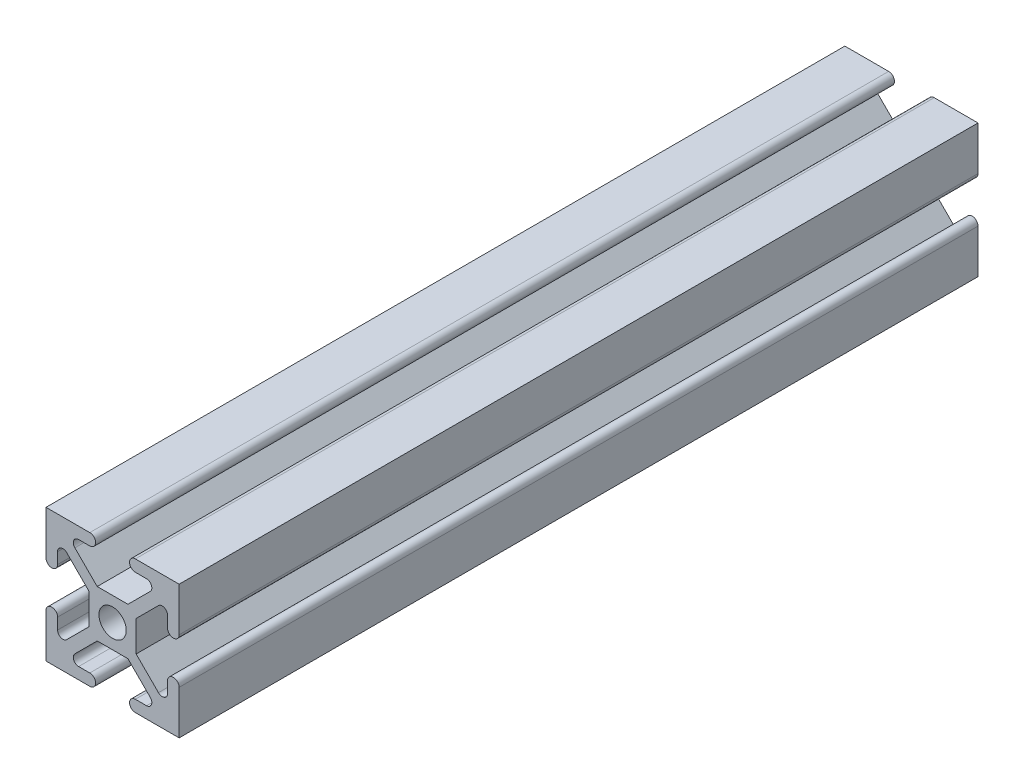
SolidWorks part; units mm, degrees
ref_plane "Front Plane" through (0, 0, 0) normal (0, 0, 1) x (1, 0, 0)
ref_plane "Top Plane" through (0, 0, 0) normal (0, 1, 0) x (1, 0, 0)
ref_plane "Right Plane" through (0, 0, 0) normal (1, 0, 0) x (0, 0, -1)
sketch "Sketch1" plane through (0, 0, 0) normal (0, 0, 1) x (1, 0, 0)
  line L2 (-12.7, -12.7) -> (-4.3434, -12.7)
  line L3 (-4.3434, -10.4902) -> (-6.4748, -10.4902)
  line L4 (-7.1932, -8.7558) -> (-2.9332, -4.4958)
  line L5 (-2.9332, -4.4958) -> (2.9332, -4.4958)
  line L6 (2.9332, -4.4958) -> (7.1932, -8.7558)
  line L7 (6.4748, -10.4902) -> (4.3434, -10.4902)
  line L8 (4.3434, -12.7) -> (12.7, -12.7)
  line L11 (12.7, -12.7) -> (12.7, -4.3434)
  line L12 (10.4902, -4.3434) -> (10.4902, -6.4748)
  line L13 (8.7558, -7.1932) -> (4.4958, -2.9332)
  line L14 (4.4958, -2.9332) -> (4.4958, 2.9332)
  line L15 (4.4958, 2.9332) -> (8.7558, 7.1932)
  line L16 (10.4902, 6.4748) -> (10.4902, 4.3434)
  line L17 (12.7, 4.3434) -> (12.7, 12.7)
  line L20 (12.7, 12.7) -> (4.3434, 12.7)
  line L21 (4.3434, 10.4902) -> (6.4748, 10.4902)
  line L22 (7.1932, 8.7558) -> (2.9332, 4.4958)
  line L23 (2.9332, 4.4958) -> (-2.9332, 4.4958)
  line L24 (-2.9332, 4.4958) -> (-7.1932, 8.7558)
  line L25 (-6.4748, 10.4902) -> (-4.3434, 10.4902)
  line L26 (-4.3434, 12.7) -> (-12.7, 12.7)
  line L29 (-12.7, 12.7) -> (-12.7, 4.3434)
  line L30 (-10.4902, 4.3434) -> (-10.4902, 6.4748)
  line L31 (-8.7558, 7.1932) -> (-4.4958, 2.9332)
  line L32 (-4.4958, 2.9332) -> (-4.4958, -2.9332)
  line L33 (-4.4958, -2.9332) -> (-8.7558, -7.1932)
  line L34 (-10.4902, -6.4748) -> (-10.4902, -4.3434)
  line L35 (-12.7, -4.3434) -> (-12.7, -12.7)
  circle A0 centre (0, 0) radius 2.6035
  arc A6 (-4.3434, -12.7) -> (-4.3434, -10.4902) centre (-4.3434, -11.5951) ccw
  arc A7 (-6.4748, -10.4902) -> (-7.1932, -8.7558) centre (-6.4748, -9.4742) cw
  arc A10 (7.1932, -8.7558) -> (6.4748, -10.4902) centre (6.4748, -9.4742) cw
  arc A11 (4.3434, -10.4902) -> (4.3434, -12.7) centre (4.3434, -11.5951) ccw
  arc A17 (12.7, -4.3434) -> (10.4902, -4.3434) centre (11.5951, -4.3434) ccw
  arc A18 (10.4902, -6.4748) -> (8.7558, -7.1932) centre (9.4742, -6.4748) cw
  arc A21 (8.7558, 7.1932) -> (10.4902, 6.4748) centre (9.4742, 6.4748) cw
  arc A22 (10.4902, 4.3434) -> (12.7, 4.3434) centre (11.5951, 4.3434) ccw
  arc A28 (4.3434, 12.7) -> (4.3434, 10.4902) centre (4.3434, 11.5951) ccw
  arc A29 (6.4748, 10.4902) -> (7.1932, 8.7558) centre (6.4748, 9.4742) cw
  arc A32 (-7.1932, 8.7558) -> (-6.4748, 10.4902) centre (-6.4748, 9.4742) cw
  arc A33 (-4.3434, 10.4902) -> (-4.3434, 12.7) centre (-4.3434, 11.5951) ccw
  arc A39 (-12.7, 4.3434) -> (-10.4902, 4.3434) centre (-11.5951, 4.3434) ccw
  arc A40 (-10.4902, 6.4748) -> (-8.7558, 7.1932) centre (-9.4742, 6.4748) cw
  arc A43 (-8.7558, -7.1932) -> (-10.4902, -6.4748) centre (-9.4742, -6.4748) cw
  arc A44 (-10.4902, -4.3434) -> (-12.7, -4.3434) centre (-11.5951, -4.3434) ccw
  point P101 (-4.4958, 0)
  point P102 (0, 4.4958)
  point P103 (4.4958, 0)
  point P127 (0, -4.4958)
extrude "Boss-Extrude1" add sketch "Sketch1" against normal blind 152.4
